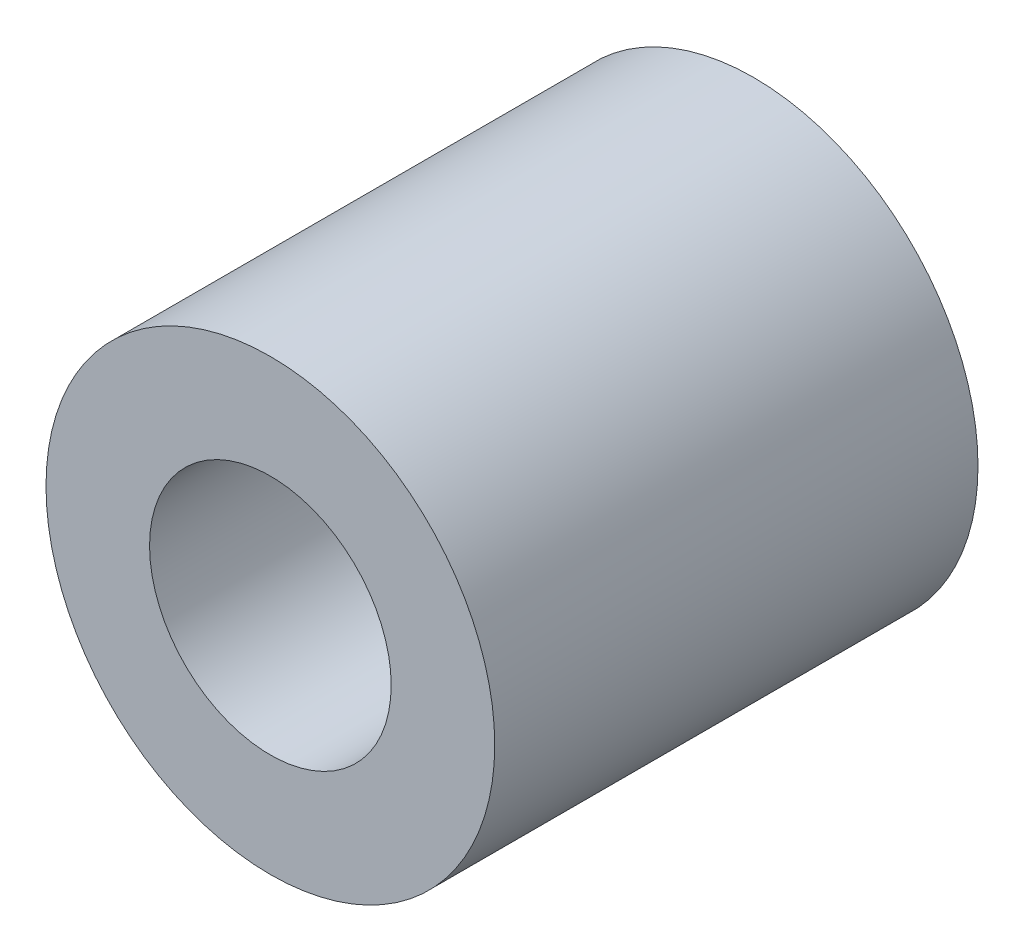
SolidWorks part; units mm, degrees
ref_plane "Plano frontal" through (0, 0, 0) normal (0, 0, 1) x (1, 0, 0)
ref_plane "Plano superior" through (0, 0, 0) normal (0, 1, 0) x (1, 0, 0)
ref_plane "Plano direito" through (0, 0, 0) normal (1, 0, 0) x (0, 0, -1)
sketch "Esboço1" plane through (0, 0, 0) normal (0, 0, 1) x (1, 0, 0)
  circle A0 centre (0, 0) radius 3.25
  dimension "D1" = 6.5
extrude "Ressalto-extrusão1" add sketch "Esboço1" along normal blind 7
sketch "Esboço2" plane through (0, 0, 0) normal (0, 0, -1) x (-1, 0, 0)
  circle A0 centre (0, 0) radius 1.75
  dimension "D1" = 3.5
extrude "Corte-extrusão1" cut sketch "Esboço2" against normal blind 7
